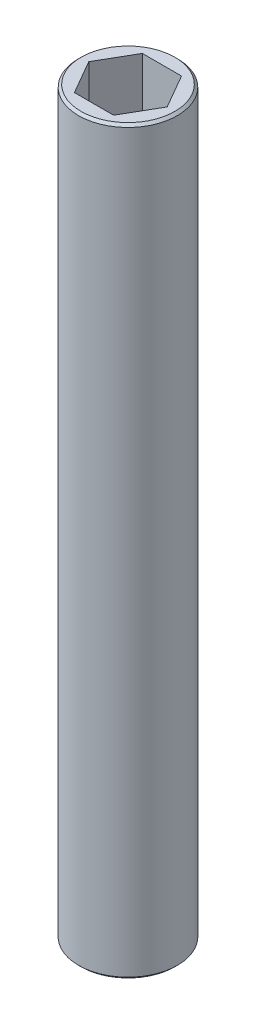
SolidWorks part; units mm, degrees
ref_plane "Front Plane" through (0, 0, 0) normal (0, 0, 1) x (1, 0, 0)
ref_plane "Top Plane" through (0, 0, 0) normal (0, 1, 0) x (1, 0, 0)
ref_plane "Right Plane" through (0, 0, 0) normal (1, 0, 0) x (0, 0, -1)
sketch "Sketch1" plane through (0, 0, 0) normal (0, 1, 0) x (1, 0, 0)
  line L1 (3.175, 0) -> (1.5875, 2.7496)
  line L2 (1.5875, 2.7496) -> (-1.5875, 2.7496)
  line L3 (-1.5875, 2.7496) -> (-3.175, 0)
  line L4 (-3.175, 0) -> (-1.5875, -2.7496)
  line L5 (-1.5875, -2.7496) -> (1.5875, -2.7496)
  line L6 (1.5875, -2.7496) -> (3.175, 0)
  circle A0 centre (0, 0) radius 4
  circle A1 centre (0, 0) radius 2.7496 construction
  dimension "D1" = 8
extrude "Boss-Extrude2" add sketch "Sketch1" along normal blind 60
chamfer "Chamfer1" distance 0.2 angle 45 2 edges at (0, 0, 4) (0, 60, 4)
